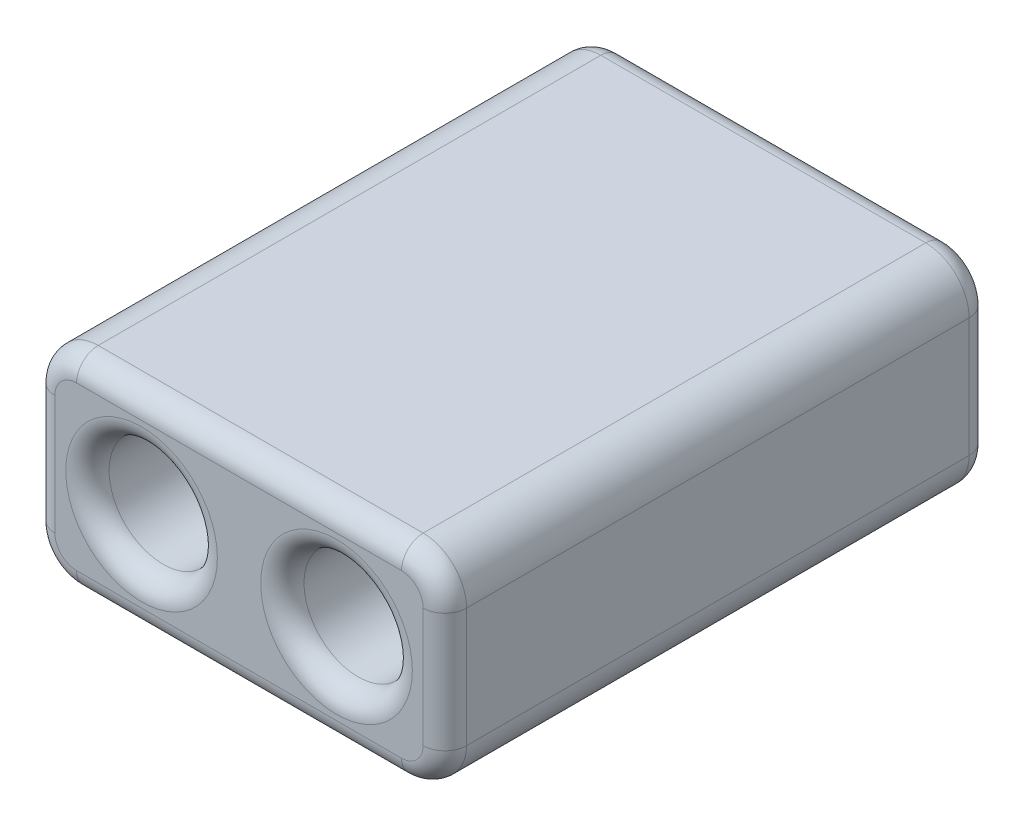
SolidWorks part; units mm, degrees
ref_plane "Спереди" through (0, 0, 0) normal (0, 0, 1) x (1, 0, 0)
ref_plane "Сверху" through (0, 0, 0) normal (0, 1, 0) x (1, 0, 0)
ref_plane "Справа" through (0, 0, 0) normal (1, 0, 0) x (0, 0, -1)
other "Configuration Table"
sketch "Эскиз1" plane through (0, 0, 0) normal (0, 0, 1) x (1, 0, 0)
  line L0 (-24.2819, 0) -> (22.6313, 0) construction
  line L1 (-9.5, 4.75) -> (9.5, 4.75)
  line L2 (-9.5, 4.75) -> (-9.5, -4.75)
  line L3 (-9.5, -4.75) -> (9.5, -4.75)
  line L4 (9.5, 4.75) -> (9.5, -4.75)
  line L5 (-9.5, 4.75) -> (9.5, -4.75) construction
  line L6 (-9.5, -4.75) -> (9.5, 4.75) construction
  line L7 (-4.5, 16.6342) -> (-4.5, -13.0763) construction
  line L8 (4.5, 16.6342) -> (4.5, -13.0763) construction
  circle A0 centre (-4.5, 0) radius 2.5
  circle A2 centre (4.5, 0) radius 2.5
  point P0 (0, 0)
  dimension "D5" = 5
  dimension "D6" = 5
  dimension "D1" = 19
  dimension "D2" = 9.5
  dimension "D3" = 5
  dimension "D4" = 5
extrude "Бобышка-Вытянуть1" add sketch "Эскиз1" along normal blind 25.2
fillet "Скругление1" radius 2 4 edges at (9.5, -4.75, 12.6) (9.5, 4.75, 12.6) (-9.5, -4.75, 12.6) (-9.5, 4.75, 12.6)
fillet "Скругление2" radius 1 10 edges at (7, 0, 25.2) (-8.9142, -4.1642, 25.2) (-9.5, 0, 25.2) (-8.9142, 4.1642, 25.2) (0, 4.75, 25.2) (8.9142, 4.1642, 25.2) (9.5, 0, 25.2) (8.9142, -4.1642, 25.2) (0, -4.75, 25.2) (-2, 0, 25.2)
fillet "Скругление3" radius 1 10 edges at (7, 0, 0) (-2, 0, 0) (8.9142, 4.1642, 0) (0, 4.75, 0) (-8.9142, 4.1642, 0) (-9.5, 0, 0) (-8.9142, -4.1642, 0) (0, -4.75, 0) (8.9142, -4.1642, 0) (9.5, 0, 0)
equation "\"D6@Эскиз1\"=\"D5@Эскиз1\""
